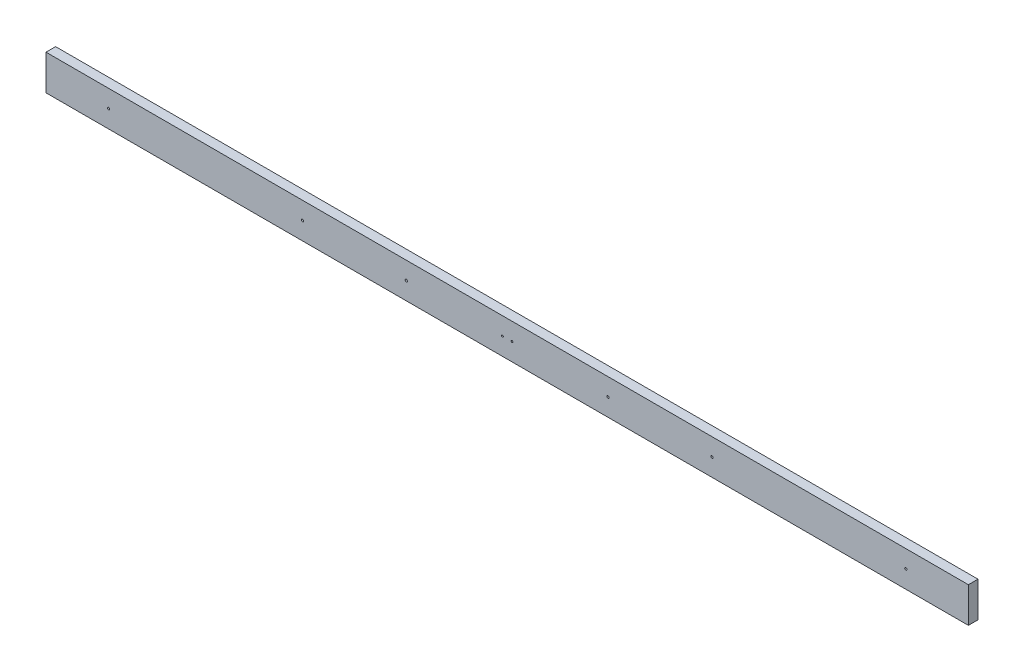
SolidWorks part; units mm, degrees
ref_plane "Front Plane" through (0, 0, 0) normal (0, 0, 1) x (1, 0, 0)
ref_plane "Top Plane" through (0, 0, 0) normal (0, 1, 0) x (1, 0, 0)
ref_plane "Right Plane" through (0, 0, 0) normal (1, 0, 0) x (0, 0, -1)
sketch "Sketch1" plane through (0, 0, 0) normal (0, 0, 1) x (1, 0, 0)
  line L1 (-1828.8, -69.85) -> (1828.8, -69.85)
  line L2 (-1828.8, -69.85) -> (-1828.8, 69.85)
  line L3 (-1828.8, 69.85) -> (1828.8, 69.85)
  line L4 (1828.8, -69.85) -> (1828.8, 69.85)
  line L5 (-1828.8, -69.85) -> (1828.8, 69.85) construction
  line L6 (-1828.8, 69.85) -> (1828.8, -69.85) construction
  point P0 (0, 0)
  dimension "D1" = 3657.6
  dimension "D2" = 139.7
extrude "Boss-Extrude1" add sketch "Sketch1" along normal blind 38.1
sketch "Sketch3" plane through (0, 0, 38.1) normal (0, 0, 1) x (1, 0, 0)
  line L0 (0, -69.85) -> (0, 69.85) construction
  line L1 (-1828.8, -69.85) -> (1828.8, -69.85) construction
  line L2 (1828.8, 69.85) -> (-1828.8, 69.85) construction
  line L3 (-25.4, -7.9375) -> (25.4, -7.9375) construction
  line L4 (-25.4, -7.9375) -> (-25.4, 7.9375) construction
  line L5 (-25.4, 7.9375) -> (25.4, 7.9375) construction
  line L6 (25.4, -7.9375) -> (25.4, 7.9375) construction
  line L7 (-19.05, 0) -> (19.05, 0) construction
  circle A0 centre (-19.05, 0) radius 3.5719
  circle A1 centre (19.05, 0) radius 3.5719
  point P14 (-25.4, 0)
  dimension "D8" = 7.1437
  dimension "D9" = 7.1437
  dimension "D1" = 15.875
  dimension "D2" = 7.9375
  dimension "D3" = 38.1
  dimension "D4" = 6.35
  dimension "D5" = 50.8
  dimension "D10" = 7.9375
extrude "Cut-Extrude2" cut sketch "Sketch3" against normal through all contours A0 | A1
sketch "Sketch4" plane through (0, 0, 38.1) normal (0, 0, 1) x (1, 0, 0)
  line L0 (0, 589.6071) -> (0, -768.8477)
  line L1 (762, 589.6071) -> (762, -768.8477)
  line L2 (0, 0) -> (-310, 0)
  line L3 (-310, 0) -> (-310, 478.8836)
  dimension "D1" = 762
  dimension "D2" = 310
sketch "Sketch5" plane through (0, 0, 38.1) normal (0, 0, 1) x (1, 0, 0)
  line L0 (-400, 0) -> (400, 0) construction
  circle A0 centre (400, 0) radius 4.4996
  circle A1 centre (-400, 0) radius 4.4996
  point P4 (0, 0)
  dimension "D2" = 8.9992
  dimension "D3" = 8.9992
  dimension "D1" = 800
extrude "Cut-Extrude3" cut sketch "Sketch5" against normal through all
sketch "Sketch6" plane through (0, 0, 38.1) normal (0, 0, 1) x (1, 0, 0)
  line L0 (1828.8, 0) -> (-1828.8, 0) construction
  line L1 (1828.8, -69.85) -> (1828.8, 69.85) construction
  line L2 (-1828.8, 69.85) -> (-1828.8, -69.85) construction
  line L3 (0, 69.85) -> (0, -69.85) construction
  line L4 (1828.8, 69.85) -> (-1828.8, 69.85) construction
  line L6 (-789.94, -403.86) -> (789.94, -403.86) construction
  line L7 (-789.94, -403.86) -> (-789.94, 403.86) construction
  line L8 (-789.94, 403.86) -> (789.94, 403.86) construction
  line L9 (789.94, -403.86) -> (789.94, 403.86) construction
  line L10 (-789.94, -403.86) -> (789.94, 403.86) construction
  line L11 (-789.94, 403.86) -> (789.94, -403.86) construction
  circle A0 centre (811.94, 0) radius 4.4996
  circle A1 centre (1580.6608, 0) radius 4.4996
  circle A3 centre (-1580.6608, 0) radius 4.4996
  circle A4 centre (-811.94, 0) radius 4.4996
  point P15 (400, 0)
  point P21 (0, 0)
  dimension "D2" = 8.9992
  dimension "D3" = 8.9992
  dimension "D1" = 768.7208
  dimension "D4" = 1579.88
  dimension "D5" = 807.72
  dimension "D6" = 22
extrude "Cut-Extrude4" cut sketch "Sketch6" against normal through all
sketch "Sketch7" plane through (0, 0, 38.1) normal (0, 0, 1) x (1, 0, 0)
  point P0 (-811.94, 0)
  point P1 (-1580.6608, 0)
  point P3 (400, 0)
  point P5 (811.94, 0)
  point P7 (1580.6608, 0)
equation "\"actuatorDistanceFromMiddle\"=310"
equation "\"D2@Sketch4\"= \"actuatorDistanceFromMiddle\""
